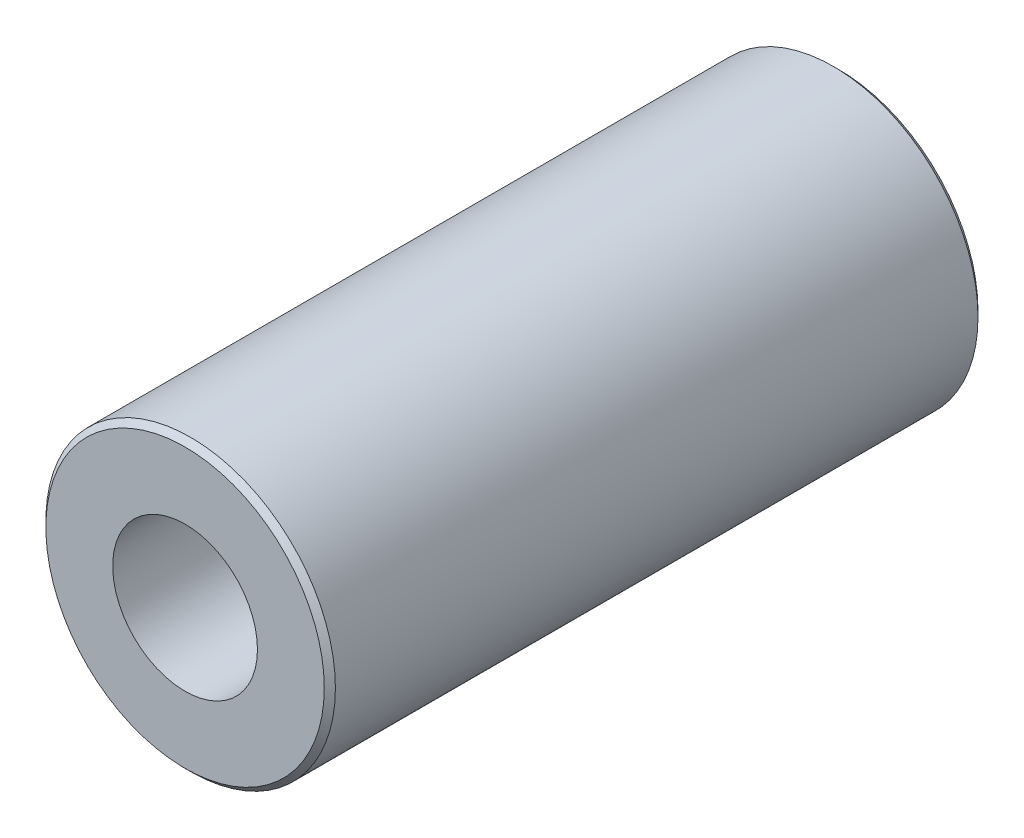
SolidWorks part; units mm, degrees
ref_plane "Front Plane" through (0, 0, 0) normal (0, 0, 1) x (1, 0, 0)
ref_plane "Top Plane" through (0, 0, 0) normal (0, 1, 0) x (1, 0, 0)
ref_plane "Right Plane" through (0, 0, 0) normal (1, 0, 0) x (0, 0, -1)
sketch "Sketch1" plane through (0, 0, 0) normal (0, 0, 1) x (1, 0, 0)
  circle A0 centre (0, 0) radius 13
  circle A1 centre (0, 0) radius 6.5
  dimension "D1" = 26
  dimension "D2" = 13
extrude "Boss-Extrude1" add sketch "Sketch1" along normal blind 58.7 contours A0 | A1
chamfer "Chamfer1" distance 0.5 angle 45 2 edges at (13, 0, 0) (13, 0, 58.7)
